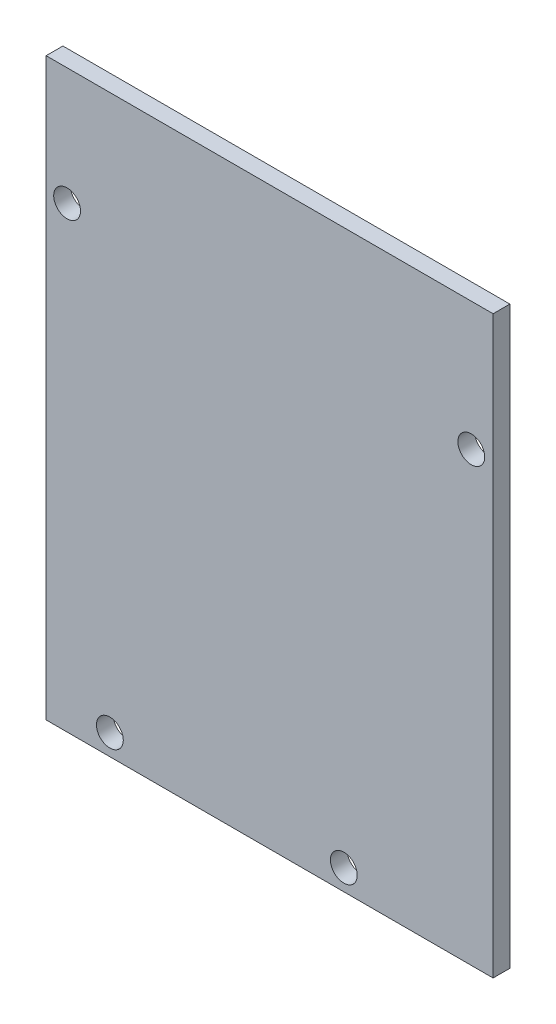
SolidWorks part; units mm, degrees
material "Silicon"
ref_plane "Front Plane" through (0, 0, 0) normal (0, 0, 1) x (1, 0, 0)
ref_plane "Top Plane" through (0, 0, 0) normal (0, 1, 0) x (1, 0, 0)
ref_plane "Right Plane" through (0, 0, 0) normal (1, 0, 0) x (0, 0, -1)
sketch "Sketch1" plane through (0, 0, 0) normal (0, 0, 1) x (1, 0, 0)
  line L0 (-19.05, -31.8) -> (8.85, -31.8) construction
  line L1 (-26.65, -34.3) -> (26.65, -34.3)
  line L2 (-26.65, -34.3) -> (-26.65, 34.3)
  line L3 (-26.65, 34.3) -> (26.65, 34.3)
  line L4 (26.65, -34.3) -> (26.65, 34.3)
  line L6 (0, 34.3) -> (0, -34.3) construction
  circle A0 centre (-19.05, -31.8) radius 1.6
  circle A1 centre (-24.15, 20.3) radius 1.6
  circle A2 centre (24.05, 19) radius 1.6
  circle A3 centre (8.85, -31.8) radius 1.6
  dimension "D10" = 3.2
  dimension "D1" = 53.3
  dimension "D2" = 68.6
  dimension "D3" = 1.3
  dimension "D4" = 2.5
  dimension "D5" = 27.9
  dimension "D6" = 15.2
  dimension "D7" = 50.8
  dimension "D8" = 14
  dimension "D9" = 5.1
extrude "Boss-Extrude1" add sketch "Sketch1" along normal blind 2
